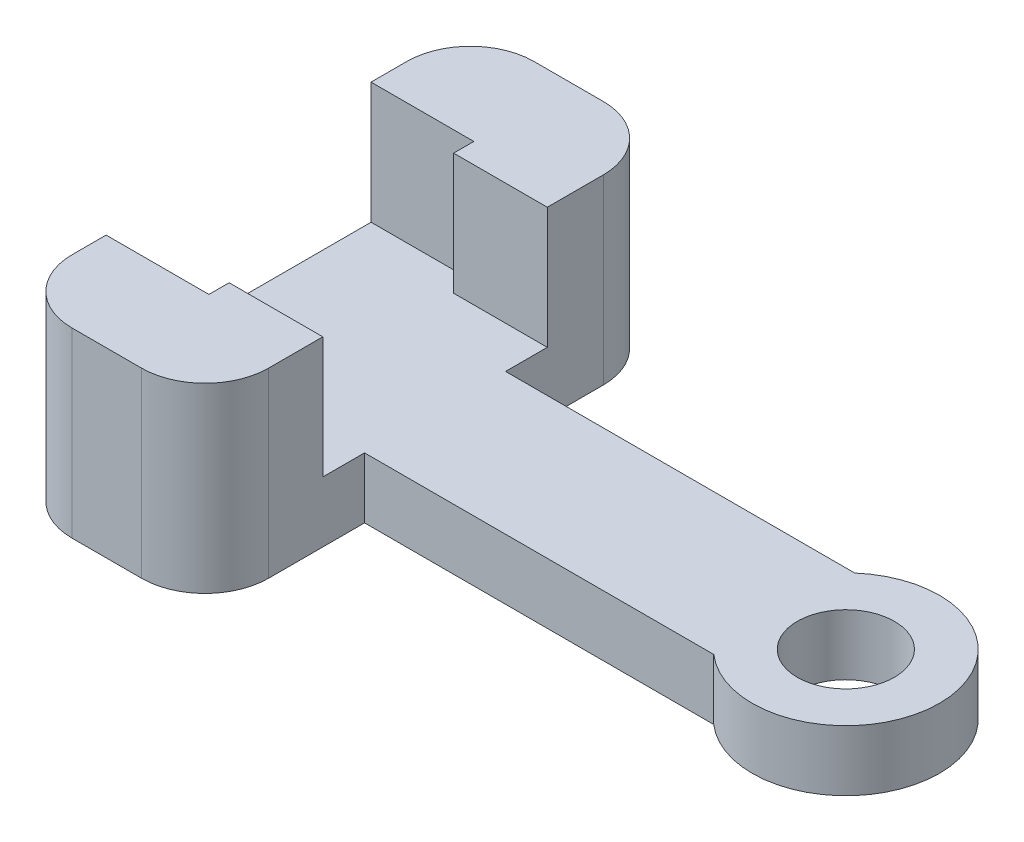
SolidWorks part; units mm, degrees
ref_plane "Alzado" through (0, 0, 0) normal (0, 0, 1) x (1, 0, 0)
ref_plane "Planta" through (0, 0, 0) normal (0, 1, 0) x (1, 0, 0)
ref_plane "Vista lateral" through (0, 0, 0) normal (1, 0, 0) x (0, 0, -1)
sketch "Croquis1" plane through (0, 0, 0) normal (0, 1, 0) x (1, 0, 0)
  line L0 (35.1175, -10.7686) -> (17.8519, -10.7686)
  line L1 (17.8519, -3.7972) -> (35.1175, -3.7972)
  line L2 (17.8519, -10.7686) -> (17.8519, -15.5115)
  line L3 (14.709, -18.6543) -> (11.2805, -18.6543)
  line L4 (8.1376, -15.5115) -> (8.1376, 1.0364)
  line L5 (11.2805, 4.1793) -> (14.709, 4.1793)
  line L6 (17.8519, 1.0364) -> (17.8519, -3.7972)
  arc A0 (14.709, -18.6543) -> (17.8519, -15.5115) centre (14.709, -15.5115) ccw
  arc A1 (8.1376, -15.5115) -> (11.2805, -18.6543) centre (11.2805, -15.5115) ccw
  arc A2 (11.2805, 4.1793) -> (8.1376, 1.0364) centre (11.2805, 1.0364) ccw
  arc A3 (17.8519, 1.0364) -> (14.709, 4.1793) centre (14.709, 1.0364) ccw
  arc A4 (35.1175, -10.7686) -> (35.1175, -3.7972) centre (38.1627, -7.2829) ccw
  circle A5 centre (38.1627, -7.2829) radius 2.4
  dimension "D1" = 4.8
extrude "Saliente-Extruir1" add sketch "Croquis1" along normal blind 3
sketch "Croquis2" plane through (0, 3, 0) normal (0, 1, 0) x (1, 0, 0)
  line L0 (13.2204, -1.7329) -> (4.9451, -1.7329) construction
  line L1 (13.2204, -1.7329) -> (17.8519, -1.7329)
  line L2 (17.8519, -3.7972) -> (17.8519, 1.0364) construction
  line L3 (13.2204, -12.8329) -> (17.8519, -12.8329)
  line L5 (38.1627, -7.2829) -> (2.3035, -7.2829) construction
  line L6 (7.1204, -0.7329) -> (13.2204, -0.7329)
  line L7 (7.1204, -0.7329) -> (7.1204, -13.8329)
  line L8 (7.1204, -13.8329) -> (13.2204, -13.8329)
  line L9 (13.2204, -0.7329) -> (13.2204, -13.8329)
  circle A4 centre (38.1627, -7.2829) radius 2.4 construction
  circle A5 centre (38.1627, -7.2829) radius 2.4
  line M7 (17.8519, -3.7972) -> (17.8519, 1.0364)
  arc M8 (17.8519, 1.0364) -> (14.709, 4.1793) centre (14.709, 1.0364) ccw
  line M9 (14.709, 4.1793) -> (11.2805, 4.1793)
  arc M10 (11.2805, 4.1793) -> (8.1376, 1.0364) centre (11.2805, 1.0364) ccw
  line M11 (8.1376, 1.0364) -> (8.1376, -15.5115)
  arc M12 (8.1376, -15.5115) -> (11.2805, -18.6543) centre (11.2805, -15.5115) ccw
  line M13 (11.2805, -18.6543) -> (14.709, -18.6543)
  arc M14 (14.709, -18.6543) -> (17.8519, -15.5115) centre (14.709, -15.5115) ccw
  line M15 (17.8519, -15.5115) -> (17.8519, -10.7686)
  dimension "D3" = 1
  dimension "D1" = 6.1
  dimension "D2" = 6.55
  dimension "D4" = 13.1
extrude "Saliente-Extruir2" add sketch "Croquis2" along normal blind 6 contours L6 L9 L1 M7 M8 M9 M10 M11 | L3 L9 L8 M11 M12 M13 M14 M15
